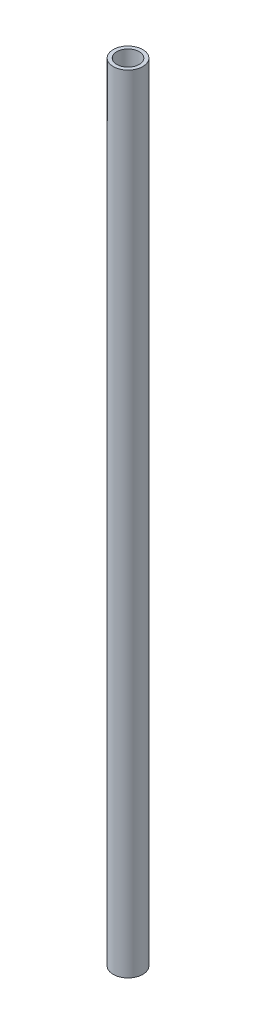
SolidWorks part; units mm, degrees
material "PTFE (general)"
ref_plane "Alzado" through (0, 0, 0) normal (0, 0, 1) x (1, 0, 0)
ref_plane "Planta" through (0, 0, 0) normal (0, 1, 0) x (1, 0, 0)
ref_plane "Vista lateral" through (0, 0, 0) normal (1, 0, 0) x (0, 0, -1)
sketch "Sketch1" plane through (0, 0, 0) normal (0, 0, 1) x (1, 0, 0)
  line L0 (1.25, -39) -> (1.65, -39)
  line L1 (1.65, -39) -> (1.65, -126.9)
  line L2 (1.65, -126.9) -> (1.25, -126.9)
  line L3 (1.25, -126.9) -> (1.25, -39)
  line L4 (0, -130.9) -> (0, -35) construction
revolve "Funda_PTFE" add sketch "Sketch1" angle 360 about L4
